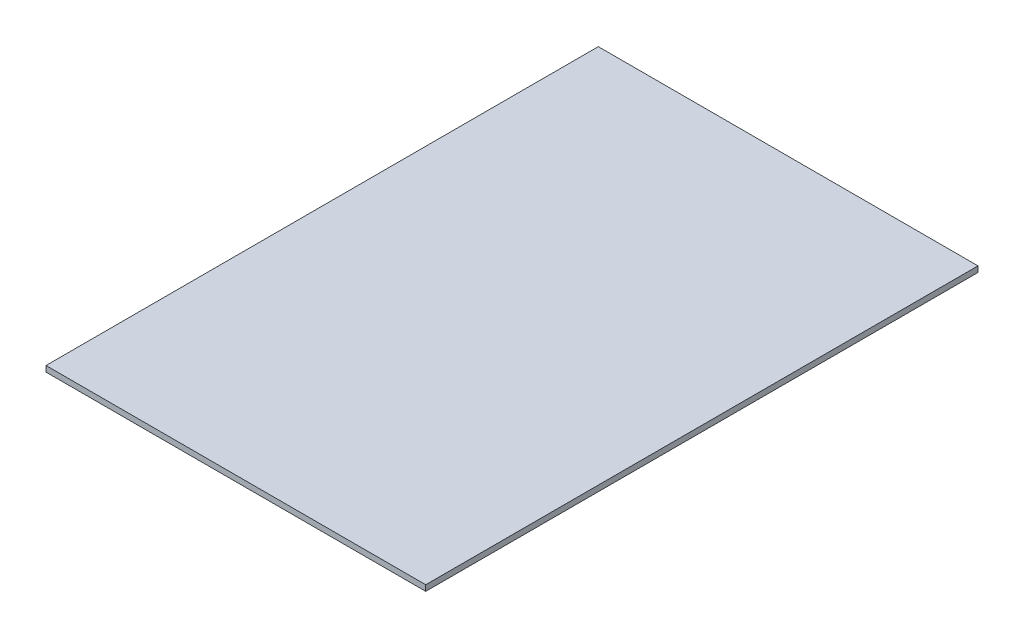
SolidWorks part; units mm, degrees
ref_plane "Front Plane" through (0, 0, 0) normal (0, 0, 1) x (1, 0, 0)
ref_plane "Top Plane" through (0, 0, 0) normal (0, 1, 0) x (1, 0, 0)
ref_plane "Right Plane" through (0, 0, 0) normal (1, 0, 0) x (0, 0, -1)
sketch "Sketch1" plane through (0, 0, 0) normal (0, 1, 0) x (1, 0, 0)
  line L1 (419.1, 609.6) -> (-419.1, 609.6)
  line L2 (419.1, 609.6) -> (419.1, -609.6)
  line L3 (419.1, -609.6) -> (-419.1, -609.6)
  line L4 (-419.1, 609.6) -> (-419.1, -609.6)
  line L5 (419.1, 609.6) -> (-419.1, -609.6) construction
  line L6 (419.1, -609.6) -> (-419.1, 609.6) construction
  point P0 (0, 0)
  dimension "D1" = 1219.2
  dimension "D2" = 838.2
extrude "Boss-Extrude1" add sketch "Sketch1" along normal blind 12.7 contours L1 L4 L3 L2
